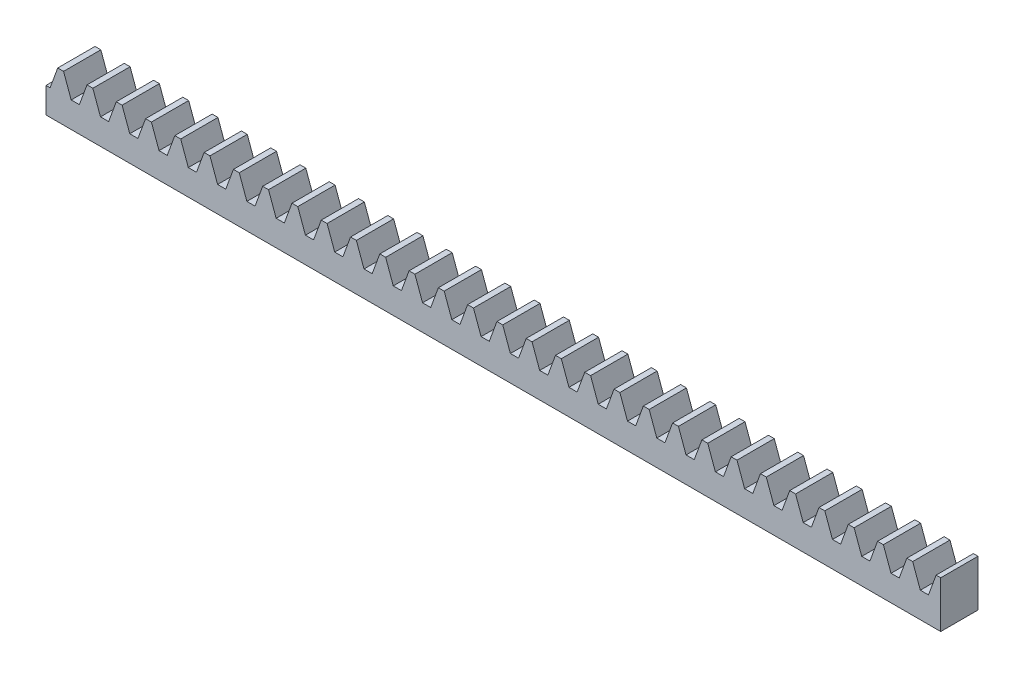
SolidWorks part; units mm, degrees
extrude "Blank" add sketch "BlankSke" against normal blind 25.4
sketch "BlankSke" plane through (0, 0, 0) normal (0, 0, 1) x (1, 0, 0)
  line L1 (0, 0) -> (609.6, 0)
  line L2 (0, 0) -> (0, 31.75)
  line L3 (0, 31.75) -> (609.6, 31.75)
  line L4 (609.6, 0) -> (609.6, 31.75)
  dimension "Length" = 609.6
  dimension "Blank_height" = 31.75
ref_plane "Plane1" through (0, 0, 0) normal (0, 0, 1) x (1, 0, 0)
ref_plane "Plane2" through (0, 0, 0) normal (0, 1, 0) x (1, 0, 0)
ref_plane "Plane3" through (0, 0, 0) normal (1, 0, 0) x (0, 0, -1)
sketch "HoldingSke" plane through (0, 0, 0) normal (0, 1, 0) x (1, 0, 0)
  line L0 (0, 0) -> (-77.8301, -65.3072)
  line L1 (-15, 0) -> (100, 0) construction
  line L2 (0, 0) -> (-2.1039, 2.3779)
  line L3 (0, 0) -> (-11.863, 4.5341)
  line L4 (0, 0) -> (7.3238, 4.5764)
  line L5 (0, 0) -> (-23.7986, -8.8762)
  line L6 (0, 0) -> (-10.5278, -7.1032)
  line L9 (-71.009, 38.7566) -> (501.8277, 247.2521)
  line L10 (-76.2, 71.12) -> (-50.8, 71.12)
  line L11 (0, 0) -> (-25.4, 0)
  line L12 (-76.2, 101.6) -> (-75.9714, 101.6)
  line L13 (24.9733, 27.94) -> (52.9518, 28.4284)
  line L14 (24.9733, 27.94) -> (24.9746, 27.94)
  line L15 (24.9733, 27.94) -> (100.4006, 29.5858)
  circle A0 centre (0, 0) radius 19.05
  circle A1 centre (0, 0) radius 12.7
  circle A2 centre (0, 0) radius 12.7
  dimension "MPH" = 25.4
  dimension "Diameter" = 38.1
  dimension "Num_teeth" = 32
  dimension "Pitch" = 101.6
  dimension "Show_teeth" = 500
  dimension "Thickness" = 12.7
  dimension "Ap" = 20
  dimension "Pitch_height" = 25.4
  dimension "Width" = 25.4
  dimension "Backlash" = 0.2286
  dimension "Addendum_fac" = 1
  dimension "Dedendum_fac" = 1.25
  dimension "Clearance_fac" = 0.25
  dimension "Dedendum_add" = 0.0013
  dimension "Length" = 609.6
sketch "TooCutSkeIll" plane through (0, 0, 0) normal (0, 0, 1) x (1, 0, 0)
  line L0 (-7.9235, 31.5829) -> (-3.1646, 18.5079)
  line L1 (-1.6716, 17.4625) -> (1.6716, 17.4625)
  line L2 (3.1646, 18.5079) -> (7.9235, 31.5829)
  line L3 (609.6, 31.75) -> (0, 31.75) construction
  line L4 (0, 0) -> (0, 64.897) construction
  line L5 (-13.208, 25.4) -> (12.954, 25.4) construction
  line L6 (0, 0) -> (609.6, 0) construction
  line L7 (5.6731, 25.4) -> (5.6731, 48.7463) construction
  line L8 (-5.6731, 25.4) -> (-5.6731, 48.7463) construction
  line L9 (8.1621, 31.75) -> (8.1621, 31.7754)
  line L10 (-8.1621, 31.75) -> (-8.1621, 31.7754)
  line L11 (-8.1621, 31.7754) -> (8.1621, 31.7754)
  arc A0 (1.6716, 17.4625) -> (3.1646, 18.5079) centre (1.6716, 19.0513) ccw
  arc A1 (-3.1646, 18.5079) -> (-1.6716, 17.4625) centre (-1.6716, 19.0513) ccw
  arc A2 (8.1621, 31.75) -> (7.9235, 31.5829) centre (8.1621, 31.496) ccw
  arc A3 (-7.9235, 31.5829) -> (-8.1621, 31.75) centre (-8.1621, 31.496) ccw
  dimension "Pitch_height" = 25.4
  dimension "Addendum_plus" = 6.3754
  dimension "Pressure_angle" = 20
  dimension "Gap_width" = 11.3462
  dimension "Dedendum" = 7.9375
extrude "ToothCutIll" [suppressed] cut sketch "TooCutSkeIll" against normal through all
sketch "TooCutSkeSim" plane through (0, 0, 0) normal (0, 0, 1) x (1, 0, 0)
  line L0 (2.7841, 17.4625) -> (-2.7841, 17.4625)
  line L1 (7.9935, 31.7754) -> (2.7841, 17.4625)
  line L2 (0, 17.4625) -> (0, 53.467) construction
  line L3 (7.9935, 31.7754) -> (-7.9935, 31.7754)
  line L6 (-7.9935, 31.7754) -> (-2.7841, 17.4625)
  line L9 (-5.6731, 25.4) -> (5.6731, 25.4) construction
  line L10 (0, 0) -> (609.6, 0) construction
  line L11 (5.6731, 25.4) -> (5.6731, 53.467) construction
  line L12 (-5.6731, 25.4) -> (-5.6731, 53.467) construction
  dimension "Pitch_height" = 25.4
  dimension "Addendum_plus" = 6.3754
  dimension "Pressure_angle" = 20
  dimension "Gap_width" = 11.3462
  dimension "Dedendum" = 7.9375
extrude "ToothCutSim" cut sketch "TooCutSkeSim" against normal through all
pattern_linear "TeethCuts" count 31 spacing 19.9491 along (1, 0, 0) of "ToothCutIll", "ToothCutSim"
equation "' \"Pitch@HoldingSke\" = 4"
equation "' \"Num_teeth@HoldingSke\" = 12"
equation "' \"Ap@HoldingSke\" =  20"
equation "' \"Ap@HoldingSke\" = 20"
equation "' \"Width@HoldingSke\" = 0.25"
equation "' \"Show_teeth@HoldingSke\" = 500"
equation "' \"Backlash@HoldingSke\" = 0.009"
equation "' \"Addendum_fac@HoldingSke\" = 1.0"
equation "' \"Dedendum_fac@HoldingSke\" = 1.25"
equation "' \"Dedendum_add@HoldingSke\" = 0.00005"
equation "' \"Clearance_fac@HoldingSke\" = 0.25"
equation "' \"Pitch_height@HoldingSke\" = 1"
equation "' \"Length@HoldingSke\" = 4.71"
equation "\"MPH@HoldingSke\" = \"Dedendum_fac@HoldingSke\" / \"Pitch@HoldingSke\" + 2 * \"Dedendum_add@HoldingSke\" + 0.002"
equation "\"MPH@HoldingSke\" = ((sgn( \"MPH@HoldingSke\" - \"Pitch_height@HoldingSke\")+1)*( \"MPH@HoldingSke\" - \"Pitch_height@HoldingSke\"))/2 + \"Pitch_height@HoldingSke\""
equation "\"Blank_height@BlankSke\" = \"Pitch_height@HoldingSke\" + \"Addendum_fac@HoldingSke\"  / \"Pitch@HoldingSke\" "
equation "\"Length@BlankSke\" =  \"Length@HoldingSke\""
equation "\"Face_width@Blank\" = \"Width@HoldingSke\""
equation "\"Pressure_angle@TooCutSkeIll\" = \"Ap@HoldingSke\""
equation "\"Addendum_plus@TooCutSkeIll\" =  \"Addendum_fac@HoldingSke\"  / \"Pitch@HoldingSke\" + 0.001"
equation "\"Dedendum@TooCutSkeIll\" = \"Dedendum_fac@HoldingSke\"  / \"Pitch@HoldingSke\""
equation "\"Pitch_height@TooCutSkeIll\" =  \"MPH@HoldingSke\""
equation "\"Gap_width@TooCutSkeIll\" = 3.14159265 / 2 / \"Pitch@HoldingSke\" + 6 * \"Backlash@HoldingSke\""
equation "\"Pressure_angle@TooCutSkeSim\" = \"Ap@HoldingSke\""
equation "\"Addendum_plus@TooCutSkeSim\" =  \"Addendum_fac@HoldingSke\"  / \"Pitch@HoldingSke\" + 0.001"
equation "\"Dedendum@TooCutSkeSim\" = \"Dedendum_fac@HoldingSke\"  / \"Pitch@HoldingSke\""
equation "\"Pitch_height@TooCutSkeSim\" =  \"MPH@HoldingSke\""
equation "\"Gap_width@TooCutSkeSim\" = 3.14159265 / 2 / \"Pitch@HoldingSke\" + 6 * \"Backlash@HoldingSke\""
equation "\"Root_fillet@TooCutSkeIll\" = \"Clearance_fac@HoldingSke\" / \"Pitch@HoldingSke\" + \"Dedendum_add@HoldingSke\""
equation "\"Break_rad@TooCutSkeIll\" = 0.02 / \"Pitch@HoldingSke\" * 2"
equation "\"Linear_pitch@TeethCuts\" = 3.14159265 / \"Pitch@HoldingSke\""
equation "\"Num_teeth@HoldingSke\" = int( ( \"Length@HoldingSke\" + 0 ) / (3.14159265 / \"Pitch@HoldingSke\")) + 0.9999  + 1"
equation " \"Num_teeth@TeethCuts\" = int( \"Show_teeth@HoldingSke\" ) + 1"
equation " \"Num_teeth@TeethCuts\" = ((sgn( \"Num_teeth@TeethCuts\" - \"Num_teeth@HoldingSke\" )-1)*( \"Num_teeth@TeethCuts\" - \"Num_teeth@HoldingSke\" ))/-2+ \"Num_teeth@HoldingSke\""
equation " \"Num_teeth@TeethCuts\" = ((sgn( \"Num_teeth@TeethCuts\" - 2.0)+1)*( \"Num_teeth@TeethCuts\" - 2.0))/2 +2.0"
